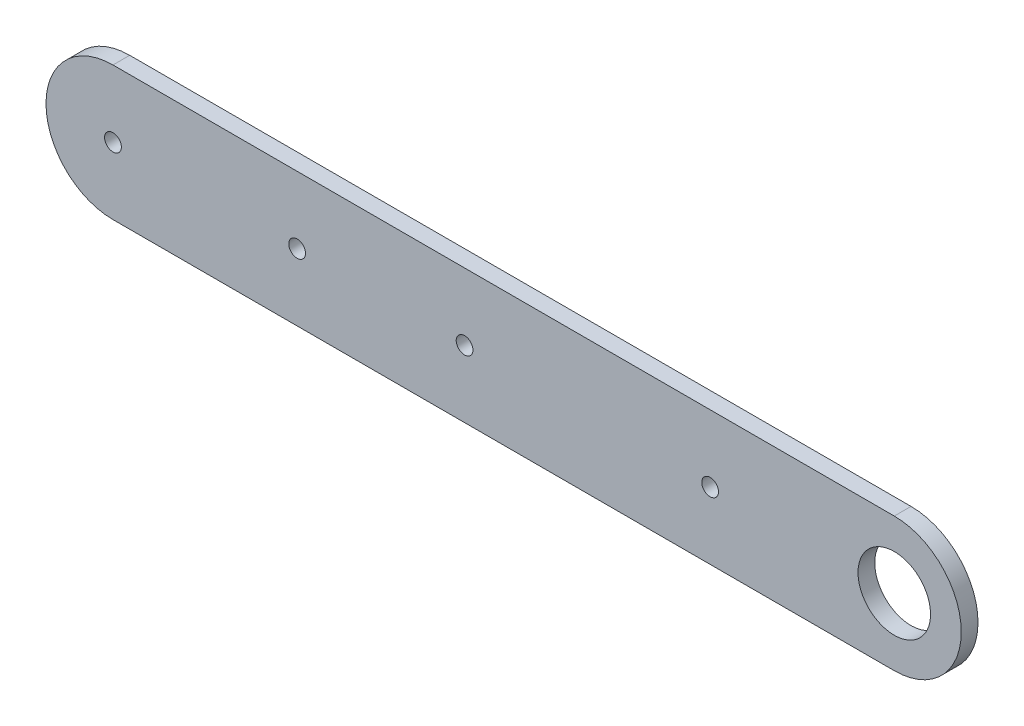
SolidWorks part; units mm, degrees
ref_plane "Plan de face" through (0, 0, 0) normal (0, 0, 1) x (1, 0, 0)
ref_plane "Plan de dessus" through (0, 0, 0) normal (0, 1, 0) x (1, 0, 0)
ref_plane "Plan de droite" through (0, 0, 0) normal (1, 0, 0) x (0, 0, -1)
sketch "Esquisse1" plane through (0, 0, 0) normal (0, 0, 1) x (1, 0, 0)
  line L0 (-107.7461, 0) -> (76.7089, 0) construction
  line L1 (-70, 12) -> (70, 12)
  line L3 (-70, -12) -> (70, -12)
  line L5 (0, 79.455) -> (0, -53.91) construction
  arc A0 (-70, 12) -> (-70, -12) centre (-70, 0) ccw
  arc A1 (70, 12) -> (70, -12) centre (70, 0) cw
  circle A4 centre (-7, 0) radius 1.5
  circle A5 centre (-70, 0) radius 1.5
  circle A6 centre (70, 0) radius 6.5
  circle A7 centre (-37, 0) radius 1.5
  circle A8 centre (37, 0) radius 1.5
  circle A9 centre (70, 0) radius 6.5 construction
  point P12 (0, 0)
  dimension "D2" = 12
  dimension "D3" = 3
  dimension "D4" = 3
  dimension "D5" = 3
  dimension "D8" = 3
  dimension "D1" = 140
  dimension "D6" = 7
  dimension "D7" = 30
  dimension "D9" = 33
extrude "Boss.-Extru.1" add sketch "Esquisse1" along normal blind 3
